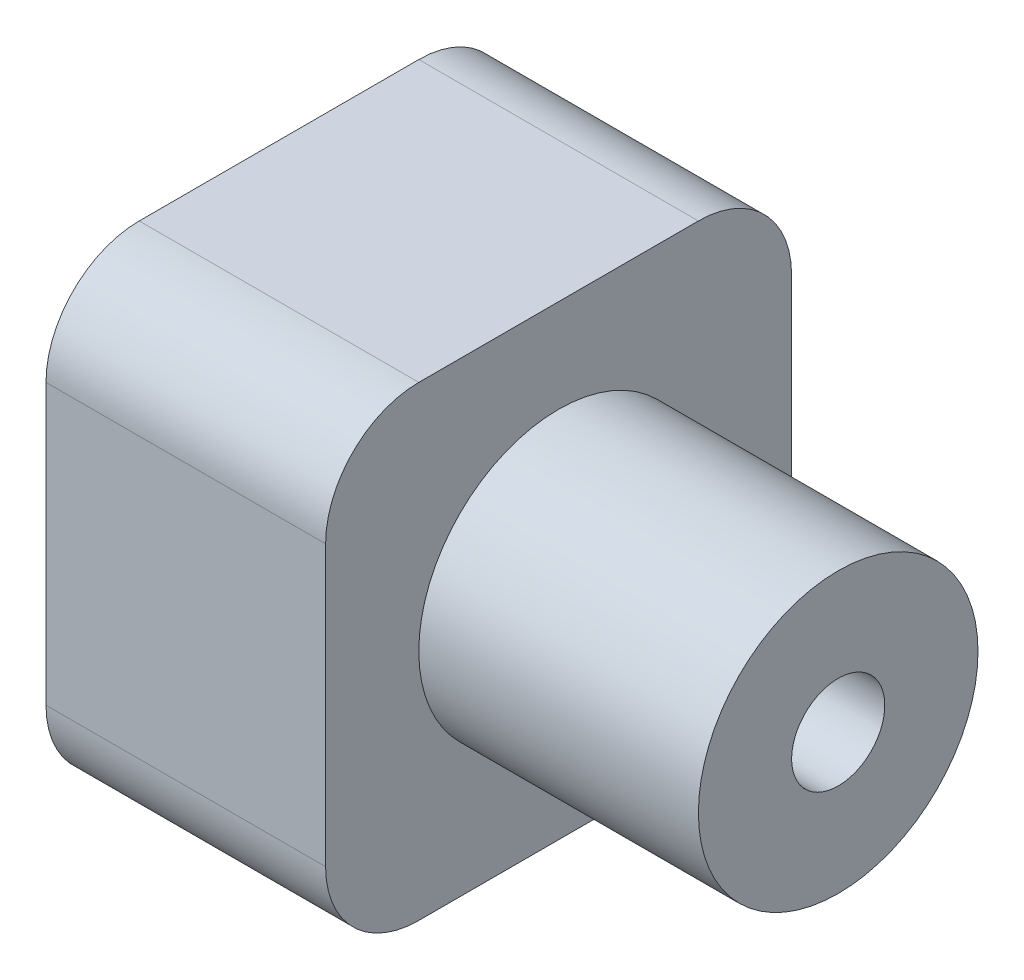
SolidWorks part; units mm, degrees
material "CMR DEFAULT - CHANGE MATERIAL"
ref_plane "XY PLANE - TOP" through (0, 0, 0) normal (0, 0, 1) x (1, 0, 0)
ref_plane "XZ PLANE - SIDE" through (0, 0, 0) normal (0, 1, 0) x (1, 0, 0)
ref_plane "YZ PLANE - FRONT" through (0, 0, 0) normal (1, 0, 0) x (0, 0, -1)
sketch "Sketch1" plane through (0, 0, 0) normal (1, 0, 0) x (0, 0, -1)
  line L1 (-15.875, -15.875) -> (15.875, -15.875)
  line L2 (-15.875, -15.875) -> (-15.875, 15.875)
  line L3 (-15.875, 15.875) -> (15.875, 15.875)
  line L4 (15.875, -15.875) -> (15.875, 15.875)
  line L5 (0, 15.875) -> (0, -15.875) construction
  line L6 (-15.875, 0) -> (15.875, 0) construction
  point P0 (0, 0)
  dimension "D1" = 31.75
  dimension "D2" = 31.75
extrude "Boss-Extrude1" add sketch "Sketch1" along normal blind 19.05
sketch "Sketch2" plane through (19.05, 0, 0) normal (1, 0, 0) x (0, 0, -1)
  circle A0 centre (0, 0) radius 9.525
  circle A1 centre (0, 0) radius 3.175
  dimension "D1" = 19.05
  dimension "D2" = 6.35
extrude "Boss-Extrude2" add sketch "Sketch2" along normal blind 19.05
fillet "Fillet1" radius 6.35 4 edges at (9.525, 15.875, -15.875) (9.525, -15.875, -15.875) (9.525, -15.875, 15.875) (9.525, 15.875, 15.875)
